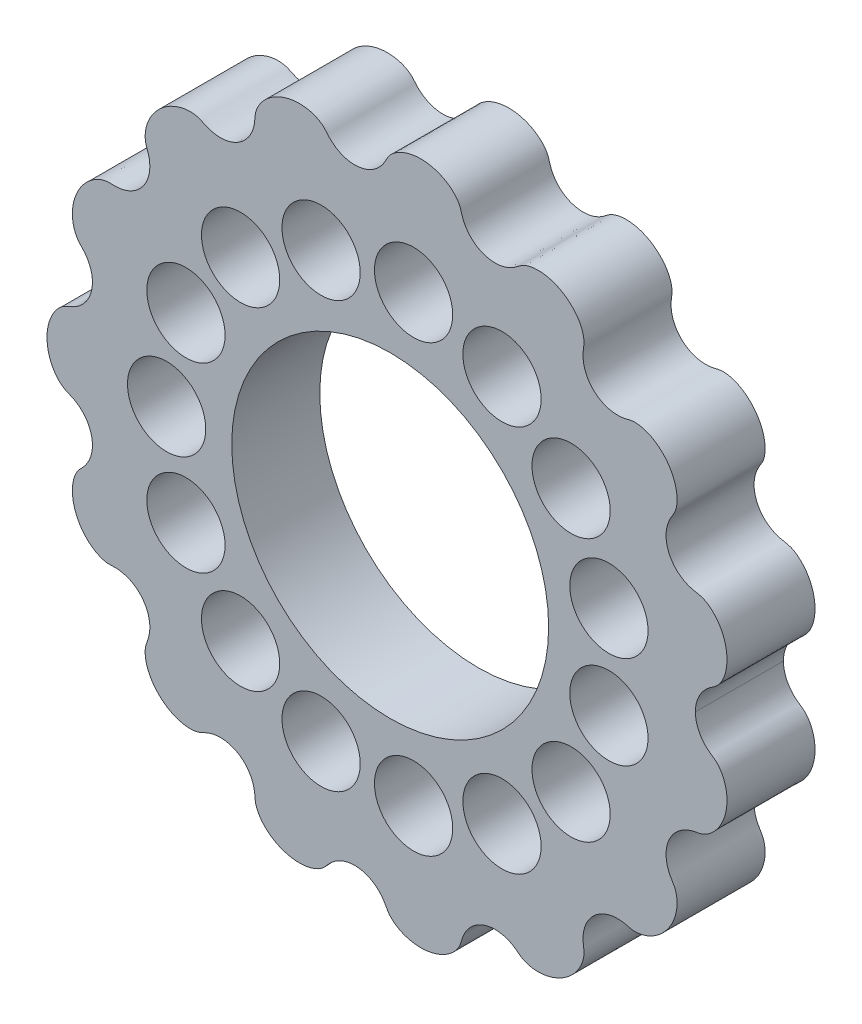
SolidWorks part; units mm, degrees
material "ABS"
ref_plane "Front Plane" through (0, 0, 0) normal (0, 0, 1) x (1, 0, 0)
ref_plane "Top Plane" through (0, 0, 0) normal (0, 1, 0) x (1, 0, 0)
ref_plane "Right Plane" through (0, 0, 0) normal (1, 0, 0) x (0, 0, -1)
sketch "Sketch2" plane through (0, 0, 0) normal (0, 0, 1) x (1, 0, 0)
  line L0 (0, 0) -> (18.3781, 0) construction
  line L1 (0, 0) -> (-12.7, 0) construction
  line L6 (0, 0) -> (-26.7529, 0) construction
  circle A0 centre (0, 0) radius 9
  circle A1 centre (-12.7, 0) radius 2.2225
  circle A10 centre (-11.602, 5.1656) radius 2.2225
  circle A11 centre (-8.498, 9.4379) radius 2.2225
  circle A12 centre (-3.9245, 12.0784) radius 2.2225
  circle A13 centre (1.3275, 12.6304) radius 2.2225
  circle A14 centre (6.35, 10.9985) radius 2.2225
  circle A15 centre (10.2745, 7.4649) radius 2.2225
  circle A16 centre (12.4225, 2.6405) radius 2.2225
  circle A17 centre (12.4225, -2.6405) radius 2.2225
  circle A18 centre (10.2745, -7.4649) radius 2.2225
  circle A19 centre (6.35, -10.9985) radius 2.2225
  circle A20 centre (1.3275, -12.6304) radius 2.2225
  circle A21 centre (-3.9245, -12.0784) radius 2.2225
  circle A22 centre (-8.498, -9.4379) radius 2.2225
  circle A23 centre (-11.602, -5.1656) radius 2.2225
  spline S0 degree 4 poles (17.3355, 0) (17.3355, 0.022) (17.3364, 0.0661) (17.3404, 0.1482) (17.3511, 0.2558) (17.3711, 0.3808) (17.4057, 0.5292) (17.4608, 0.6993) (17.5431, 0.8835) (17.6435, 1.0585) (17.7605, 1.2214) (17.8868, 1.3648) (18.0188, 1.4893) (18.152, 1.5968) (18.284, 1.6887) (18.4068, 1.7677) (18.5101, 1.8484) (18.6114, 1.9469) (18.7103, 2.0649) (18.8119, 2.2151) (18.9788, 2.5318) (19.1284, 3.0222) (19.1691, 3.6778) (19.0197, 4.3616) (18.7658, 4.895) (18.5029, 5.2499) (18.2908, 5.4667) (18.0909, 5.625) (17.936, 5.7218) (17.7996, 5.7887) (17.6725, 5.8365) (17.5499, 5.8688) (17.4098, 5.8911) (17.2557, 5.9192) (17.0952, 5.96) (16.9297, 6.0153) (16.7182, 6.1072) (16.4691, 6.2552) (16.2082, 6.4745) (15.9606, 6.7851) (15.777, 7.1489) (15.6723, 7.5479) (15.6565, 7.9135) (15.698, 8.2228) (15.7641, 8.4609) (15.8302, 8.6338) (15.9057, 8.7908) (15.9865, 8.9326) (16.0678, 9.0566) (16.1353, 9.1714) (16.1945, 9.3026) (16.2418, 9.4503) (16.2782, 9.6273) (16.3107, 9.9874) (16.2563, 10.505) (16.0255, 11.1471) (15.5906, 11.7382) (15.1094, 12.1391) (14.6943, 12.3573) (14.4005, 12.4606) (14.1434, 12.5135) (13.9574, 12.5296) (13.7955, 12.524) (13.646, 12.4991) (13.511, 12.464) (13.3614, 12.4266) (13.1944, 12.3981) (13.0154, 12.381) (12.8253, 12.3797) (12.5738, 12.4026) (12.2655, 12.4754) (11.9355, 12.6193) (11.6068, 12.8541) (11.3394, 13.1429) (11.1399, 13.4677) (11.021, 13.7866) (10.9639, 14.0781) (10.9493, 14.3167) (10.9547, 14.4996) (10.9719, 14.6649) (10.9953, 14.8125) (11.0138, 14.9707) (11.0079, 15.1399) (10.9777, 15.3255) (10.9213, 15.5246) (10.826, 15.7601) (10.6793, 16.0232) (10.4202, 16.3707) (10.0022, 16.7545) (9.5088, 17.0394) (8.9674, 17.2095) (8.5368, 17.2602) (8.2356, 17.2556) (7.9841, 17.2204) (7.7834, 17.1697) (7.6075, 17.1031) (7.4581, 17.0235) (7.3304, 16.9284) (7.2142, 16.8343) (7.0797, 16.7369) (6.924, 16.6408) (6.7101, 16.534) (6.4291, 16.4378) (6.0935, 16.3813) (5.7124, 16.3917) (5.3285, 16.4789) (4.9609, 16.6461) (4.6712, 16.86) (4.454, 17.0906) (4.3085, 17.2969) (4.2145, 17.4622) (4.1399, 17.6257) (4.0811, 17.7846) (4.0386, 17.9329) (4.0016, 18.0673) (3.9484, 18.2093) (3.8722, 18.3523) (3.7653, 18.5053) (3.5909, 18.7015) (3.3546, 18.9043) (2.9581, 19.1547) (2.3703, 19.371) (1.6409, 19.4521) (0.9694, 19.3309) (0.494, 19.1192) (0.1984, 18.911) (0.0633, 18.791) (-0.0409, 18.6762) (-0.125, 18.5593) (-0.1906, 18.4434) (-0.2573, 18.311) (-0.3397, 18.1701) (-0.438, 18.0263) (-0.5547, 17.8825) (-0.7278, 17.7063) (-0.975, 17.5157) (-1.2995, 17.3465) (-1.6974, 17.2377) (-2.1042, 17.2148) (-2.4971, 17.274) (-2.8174, 17.3902) (-3.0701, 17.532) (-3.2554, 17.6692) (-3.3861, 17.7848) (-3.5017, 17.9035) (-3.6031, 18.0229) (-3.6924, 18.133) (-3.7817, 18.2231) (-3.8867, 18.3093) (-4.0128, 18.3939) (-4.1741, 18.4797) (-4.4111, 18.5737) (-4.7049, 18.6489) (-5.1436, 18.6992) (-5.7326, 18.6523) (-6.3023, 18.4708) (-6.8174, 18.1627) (-7.1549, 17.854) (-7.3507, 17.6166) (-7.4876, 17.3991) (-7.5669, 17.236) (-7.6196, 17.0913) (-7.6543, 16.9544) (-7.6725, 16.8247) (-7.6795, 16.6788) (-7.6932, 16.5185) (-7.7196, 16.3494) (-7.7615, 16.1729) (-7.8384, 15.9445) (-7.9726, 15.6719) (-8.1825, 15.3834) (-8.486, 15.1097) (-8.8424, 14.9039) (-9.2312, 14.778) (-9.586, 14.7404) (-9.8891, 14.7605) (-10.1254, 14.8081) (-10.2992, 14.8601) (-10.4589, 14.9217) (-10.6045, 14.9901) (-10.7343, 15.0569) (-10.8558, 15.106) (-10.9917, 15.1445) (-11.1433, 15.1711) (-11.3243, 15.184) (-11.5811, 15.1742) (-11.8846, 15.1233) (-12.3207, 14.9854) (-12.845, 14.6933) (-13.2871, 14.2907) (-13.6221, 13.8041) (-13.798, 13.399) (-13.8798, 13.107) (-13.9168, 12.8547) (-13.9232, 12.6721) (-13.913, 12.5206) (-13.8908, 12.3866) (-13.8575, 12.2643) (-13.8068, 12.1318) (-13.7541, 11.9843) (-13.7091, 11.8249) (-13.6743, 11.6539) (-13.6481, 11.4248) (-13.6517, 11.135) (-13.7112, 10.7995) (-13.8564, 10.4297) (-14.0796, 10.0888) (-14.3728, 9.7987) (-14.6815, 9.6022) (-14.9702, 9.4834) (-15.2094, 9.4216) (-15.3922, 9.3924) (-15.5659, 9.3793) (-15.7291, 9.3784) (-15.8771, 9.3868) (-16.0104, 9.3879) (-16.1536, 9.3736) (-16.3051, 9.3407) (-16.4766, 9.2837) (-16.8047, 9.1318) (-17.2258, 8.8259) (-17.6664, 8.3049) (-17.9609, 7.6328) (-18.0675, 7.0156) (-18.0489, 6.547) (-17.9914, 6.2409) (-17.9088, 5.9918) (-17.8296, 5.8227) (-17.7439, 5.6853) (-17.661, 5.5845) (-17.5943, 5.5141) (-17.5308, 5.4492) (-17.4724, 5.3879) (-17.4019, 5.309) (-17.3219, 5.2104) (-17.23, 5.0812) (-17.1338, 4.9172) (-17.0279, 4.688) (-16.9368, 4.3846) (-16.8964, 4.0268) (-16.9354, 3.6248) (-17.0518, 3.2488) (-17.2333, 2.9135) (-17.4501, 2.6512) (-17.6739, 2.4559) (-17.8733, 2.324) (-18.0344, 2.2373) (-18.1861, 2.1695) (-18.3256, 2.1159) (-18.4719, 2.0529) (-18.6155, 1.9632) (-18.7611, 1.8442) (-18.9053, 1.6958) (-19.0616, 1.4955) (-19.192, 1.2774) (-19.2944, 1.0552) (-19.3719, 0.8334) (-19.4214, 0.6522) (-19.4539, 0.4901) (-19.4739, 0.3535) (-19.4855, 0.2338) (-19.4917, 0.1326) (-19.494, 0.0608) (-19.4945, 0.0203) (-19.4945, 0) knots 0.068176 0.068176 0.068176 0.068176 0.068176 0.069432 0.070688 0.071943 0.073199 0.07572 0.07824 0.080694 0.083148 0.08563 0.088113 0.090095 0.092076 0.094058 0.09604 0.097282 0.098525 0.10101 0.103607 0.106204 0.116127 0.126049 0.135533 0.140274 0.145016 0.147725 0.150434 0.152813 0.154002 0.155191 0.157122 0.159052 0.160982 0.162912 0.165276 0.167641 0.172327 0.177141 0.181961 0.187087 0.192259 0.197312 0.199858 0.202403 0.204413 0.206423 0.208433 0.210443 0.211712 0.212982 0.21552 0.21806 0.2206 0.230761 0.24092 0.251197 0.256273 0.261349 0.26392 0.26649 0.269181 0.270527 0.271873 0.273958 0.276043 0.278128 0.280213 0.282806 0.285398 0.290549 0.295754 0.300413 0.305158 0.309821 0.314419 0.31708 0.319741 0.321582 0.323422 0.325263 0.327104 0.329419 0.331734 0.334508 0.337282 0.34191 0.346537 0.355792 0.365046 0.369673 0.374301 0.377075 0.379849 0.382164 0.384479 0.38632 0.388161 0.390001 0.391842 0.394503 0.397165 0.401762 0.406425 0.41117 0.415829 0.421034 0.426185 0.428777 0.43137 0.433455 0.43554 0.437625 0.439711 0.441056 0.442402 0.445093 0.447663 0.450234 0.45531 0.460386 0.470663 0.480822 0.490983 0.493523 0.496063 0.498601 0.499871 0.50114 0.50315 0.50516 0.50717 0.50918 0.511725 0.514271 0.519324 0.524496 0.529623 0.534442 0.539256 0.543942 0.546307 0.548671 0.550601 0.552531 0.554461 0.556392 0.557581 0.55877 0.561149 0.563858 0.566567 0.571309 0.57605 0.585534 0.595456 0.600418 0.605379 0.607976 0.610573 0.613058 0.614301 0.615543 0.617525 0.619507 0.621488 0.62347 0.625953 0.628436 0.633343 0.638384 0.643407 0.648429 0.653471 0.658378 0.660861 0.663343 0.665325 0.667307 0.669288 0.67127 0.672513 0.673755 0.676241 0.678838 0.681434 0.686396 0.691357 0.701279 0.710763 0.715505 0.720246 0.722955 0.725664 0.728043 0.729232 0.730422 0.732352 0.734282 0.736212 0.738142 0.740507 0.742871 0.747557 0.752371 0.757191 0.762317 0.76749 0.772543 0.775088 0.777634 0.779644 0.781654 0.783663 0.785673 0.786943 0.788212 0.790751 0.793291 0.79583 0.805991 0.816151 0.826427 0.831503 0.83658 0.83915 0.841721 0.844412 0.845757 0.847103 0.848145 0.849188 0.85023 0.851273 0.853358 0.855443 0.858036 0.860629 0.865779 0.870984 0.875643 0.880389 0.885051 0.889649 0.89231 0.894972 0.896812 0.898653 0.900493 0.902334 0.904649 0.906964 0.909738 0.912513 0.91714 0.919454 0.921767 0.924081 0.926394 0.927551 0.928708 0.929865 0.931022 0.931022 0.931022 0.931022 0.931022
  spline S2 degree 4 poles (18.7633, 4.8586) (18.8566, 4.6949) (19.0126, 4.3502) (19.1295, 3.8883) (19.146, 3.3193) (19.0772, 2.8818) (18.9864, 2.5766) (18.8762, 2.3288) (18.7622, 2.1358) (18.6445, 1.9821) (18.5309, 1.8645) (18.4127, 1.7724) (18.2984, 1.6976) (18.1631, 1.6053) (18.0131, 1.4864) (17.8313, 1.3119) (17.6678, 1.103) (17.5417, 0.8858) (17.4501, 0.6688) (17.4009, 0.5099) (17.3699, 0.3735) (17.3511, 0.2546) (17.3405, 0.1491) (17.3351, 0.0404) (17.335, -0.0379) (17.3404, -0.1482) (17.3511, -0.2558) (17.3711, -0.3808) (17.4057, -0.5292) (17.4608, -0.6993) (17.5431, -0.8835) (17.6435, -1.0585) (17.7605, -1.2214) (17.8868, -1.3648) (18.0188, -1.4893) (18.152, -1.5968) (18.284, -1.6887) (18.4068, -1.7677) (18.5101, -1.8484) (18.6114, -1.9469) (18.7103, -2.0649) (18.8119, -2.2151) (18.9788, -2.5318) (19.1284, -3.0222) (19.1691, -3.6778) (19.0197, -4.3616) (18.7658, -4.895) (18.5029, -5.2499) (18.2908, -5.4667) (18.0909, -5.625) (17.936, -5.7218) (17.7996, -5.7887) (17.6725, -5.8365) (17.5499, -5.8688) (17.4098, -5.8911) (17.2557, -5.9192) (17.0952, -5.96) (16.9297, -6.0153) (16.7182, -6.1072) (16.4691, -6.2552) (16.2082, -6.4745) (15.9606, -6.7851) (15.777, -7.1489) (15.6723, -7.5479) (15.6565, -7.9135) (15.698, -8.2228) (15.7641, -8.4609) (15.8302, -8.6338) (15.9057, -8.7908) (15.9865, -8.9326) (16.0678, -9.0566) (16.1353, -9.1714) (16.1945, -9.3026) (16.2418, -9.4503) (16.2782, -9.6273) (16.3107, -9.9874) (16.2563, -10.505) (16.0255, -11.1471) (15.5906, -11.7382) (15.1094, -12.1391) (14.6943, -12.3573) (14.4005, -12.4606) (14.1434, -12.5135) (13.9574, -12.5296) (13.7955, -12.524) (13.646, -12.4991) (13.511, -12.464) (13.3614, -12.4266) (13.1944, -12.3981) (13.0154, -12.381) (12.8253, -12.3797) (12.5738, -12.4026) (12.2655, -12.4754) (11.9355, -12.6193) (11.6068, -12.8541) (11.3394, -13.1429) (11.1399, -13.4677) (11.021, -13.7866) (10.9639, -14.0781) (10.9493, -14.3167) (10.9547, -14.4996) (10.9719, -14.6649) (10.9953, -14.8125) (11.0138, -14.9707) (11.0079, -15.1399) (10.9777, -15.3255) (10.9213, -15.5246) (10.826, -15.7601) (10.6793, -16.0232) (10.4202, -16.3707) (10.0022, -16.7545) (9.5088, -17.0394) (8.9674, -17.2095) (8.5368, -17.2602) (8.2356, -17.2556) (7.9841, -17.2204) (7.7834, -17.1697) (7.6075, -17.1031) (7.4581, -17.0235) (7.3304, -16.9284) (7.2142, -16.8343) (7.0797, -16.7369) (6.924, -16.6408) (6.7101, -16.534) (6.4291, -16.4378) (6.0935, -16.3813) (5.7124, -16.3917) (5.3285, -16.4789) (4.9609, -16.6461) (4.6712, -16.86) (4.454, -17.0906) (4.3085, -17.2969) (4.2145, -17.4622) (4.1399, -17.6257) (4.0811, -17.7846) (4.0386, -17.9329) (4.0016, -18.0673) (3.9484, -18.2093) (3.8722, -18.3523) (3.7653, -18.5053) (3.5909, -18.7015) (3.3546, -18.9043) (2.9581, -19.1547) (2.3703, -19.371) (1.6409, -19.4521) (0.9694, -19.3309) (0.494, -19.1192) (0.1984, -18.911) (0.0633, -18.791) (-0.0409, -18.6762) (-0.125, -18.5593) (-0.1906, -18.4434) (-0.2573, -18.311) (-0.3397, -18.1701) (-0.438, -18.0263) (-0.5547, -17.8825) (-0.7278, -17.7063) (-0.975, -17.5157) (-1.2995, -17.3465) (-1.6974, -17.2377) (-2.1042, -17.2148) (-2.4971, -17.274) (-2.8174, -17.3902) (-3.0701, -17.532) (-3.2554, -17.6692) (-3.3861, -17.7848) (-3.5017, -17.9035) (-3.6031, -18.0229) (-3.6924, -18.133) (-3.7817, -18.2231) (-3.8867, -18.3093) (-4.0128, -18.3939) (-4.1741, -18.4797) (-4.4111, -18.5737) (-4.7049, -18.6489) (-5.1436, -18.6992) (-5.7326, -18.6523) (-6.3023, -18.4708) (-6.8174, -18.1627) (-7.1549, -17.854) (-7.3507, -17.6166) (-7.4876, -17.3991) (-7.5669, -17.236) (-7.6196, -17.0913) (-7.6543, -16.9544) (-7.6725, -16.8247) (-7.6795, -16.6788) (-7.6932, -16.5185) (-7.7196, -16.3494) (-7.7615, -16.1729) (-7.8384, -15.9445) (-7.9726, -15.6719) (-8.1825, -15.3834) (-8.486, -15.1097) (-8.8424, -14.9039) (-9.2312, -14.778) (-9.586, -14.7404) (-9.8891, -14.7605) (-10.1254, -14.8081) (-10.2992, -14.8601) (-10.4589, -14.9217) (-10.6045, -14.9901) (-10.7343, -15.0569) (-10.8558, -15.106) (-10.9917, -15.1445) (-11.1433, -15.1711) (-11.3243, -15.184) (-11.5811, -15.1742) (-11.8846, -15.1233) (-12.3207, -14.9854) (-12.845, -14.6933) (-13.2871, -14.2907) (-13.6221, -13.8041) (-13.798, -13.399) (-13.8798, -13.107) (-13.9168, -12.8547) (-13.9232, -12.6721) (-13.913, -12.5206) (-13.8908, -12.3866) (-13.8575, -12.2643) (-13.8068, -12.1318) (-13.7541, -11.9843) (-13.7091, -11.8249) (-13.6743, -11.6539) (-13.6481, -11.4248) (-13.6517, -11.135) (-13.7112, -10.7995) (-13.8564, -10.4297) (-14.0796, -10.0888) (-14.3728, -9.7987) (-14.6815, -9.6022) (-14.9702, -9.4834) (-15.2094, -9.4216) (-15.3922, -9.3924) (-15.5659, -9.3793) (-15.7291, -9.3784) (-15.8771, -9.3868) (-16.0104, -9.3879) (-16.1536, -9.3736) (-16.3051, -9.3407) (-16.4766, -9.2837) (-16.8047, -9.1318) (-17.2258, -8.8259) (-17.6664, -8.3049) (-17.9609, -7.6328) (-18.0675, -7.0156) (-18.0489, -6.547) (-17.9914, -6.2409) (-17.9088, -5.9918) (-17.8296, -5.8227) (-17.7439, -5.6853) (-17.661, -5.5845) (-17.5943, -5.5141) (-17.5308, -5.4492) (-17.4724, -5.3879) (-17.4019, -5.309) (-17.3219, -5.2104) (-17.23, -5.0812) (-17.1338, -4.9172) (-17.0279, -4.688) (-16.9368, -4.3846) (-16.8964, -4.0268) (-16.9354, -3.6248) (-17.0518, -3.2488) (-17.2333, -2.9135) (-17.4501, -2.6512) (-17.6739, -2.4559) (-17.8733, -2.324) (-18.0344, -2.2373) (-18.1861, -2.1695) (-18.3256, -2.1159) (-18.4719, -2.0529) (-18.6155, -1.9632) (-18.7611, -1.8442) (-18.9053, -1.6958) (-19.0616, -1.4955) (-19.192, -1.2774) (-19.2944, -1.0552) (-19.3719, -0.8334) (-19.4214, -0.6522) (-19.4539, -0.4901) (-19.4739, -0.3535) (-19.4855, -0.2338) (-19.4917, -0.1326) (-19.4948, -0.037) (-19.4948, 0.0364) (-19.4917, 0.1316) (-19.4856, 0.232) (-19.4742, 0.351) (-19.4544, 0.4867) (-19.4225, 0.6475) (-19.3737, 0.8276) (-19.2973, 1.048) (-19.1964, 1.2688) (-19.0681, 1.4857) (-18.9143, 1.6852) (-18.7725, 1.8335) (-18.6329, 1.9498) (-18.5003, 2.0363) (-18.3706, 2.0977) (-18.2504, 2.1445) (-18.1062, 2.2036) (-17.9419, 2.2842) (-17.733, 2.4112) (-17.4958, 2.6047) (-17.2705, 2.8611) (-17.0558, 3.2276) (-16.9099, 3.6914) (-16.895, 4.0854) (-16.9436, 4.3777) (-16.984, 4.5249) knots 0 0 0 0 0 0.009284 0.018569 0.023211 0.027854 0.031033 0.034213 0.036543 0.038874 0.040556 0.042237 0.043918 0.0456 0.048628 0.051656 0.056303 0.058626 0.060948 0.063272 0.064433 0.065595 0.066886 0.068176 0.069432 0.070688 0.071943 0.073199 0.07572 0.07824 0.080694 0.083148 0.08563 0.088113 0.090095 0.092076 0.094058 0.09604 0.097282 0.098525 0.10101 0.103607 0.106204 0.116127 0.126049 0.135533 0.140274 0.145016 0.147725 0.150434 0.152813 0.154002 0.155191 0.157122 0.159052 0.160982 0.162912 0.165276 0.167641 0.172327 0.177141 0.181961 0.187087 0.192259 0.197312 0.199858 0.202403 0.204413 0.206423 0.208433 0.210443 0.211712 0.212982 0.21552 0.21806 0.2206 0.230761 0.24092 0.251197 0.256273 0.261349 0.26392 0.26649 0.269181 0.270527 0.271873 0.273958 0.276043 0.278128 0.280213 0.282806 0.285398 0.290549 0.295754 0.300413 0.305158 0.309821 0.314419 0.31708 0.319741 0.321582 0.323422 0.325263 0.327104 0.329419 0.331734 0.334508 0.337282 0.34191 0.346537 0.355792 0.365046 0.369673 0.374301 0.377075 0.379849 0.382164 0.384479 0.38632 0.388161 0.390001 0.391842 0.394503 0.397165 0.401762 0.406425 0.41117 0.415829 0.421034 0.426185 0.428777 0.43137 0.433455 0.43554 0.437625 0.439711 0.441056 0.442402 0.445093 0.447663 0.450234 0.45531 0.460386 0.470663 0.480822 0.490983 0.493523 0.496063 0.498601 0.499871 0.50114 0.50315 0.50516 0.50717 0.50918 0.511725 0.514271 0.519324 0.524496 0.529623 0.534442 0.539256 0.543942 0.546307 0.548671 0.550601 0.552531 0.554461 0.556392 0.557581 0.55877 0.561149 0.563858 0.566567 0.571309 0.57605 0.585534 0.595456 0.600418 0.605379 0.607976 0.610573 0.613058 0.614301 0.615543 0.617525 0.619507 0.621488 0.62347 0.625953 0.628436 0.633343 0.638384 0.643407 0.648429 0.653471 0.658378 0.660861 0.663343 0.665325 0.667307 0.669288 0.67127 0.672513 0.673755 0.676241 0.678838 0.681434 0.686396 0.691357 0.701279 0.710763 0.715505 0.720246 0.722955 0.725664 0.728043 0.729232 0.730422 0.732352 0.734282 0.736212 0.738142 0.740507 0.742871 0.747557 0.752371 0.757191 0.762317 0.76749 0.772543 0.775088 0.777634 0.779644 0.781654 0.783663 0.785673 0.786943 0.788212 0.790751 0.793291 0.79583 0.805991 0.816151 0.826427 0.831503 0.83658 0.83915 0.841721 0.844412 0.845757 0.847103 0.848145 0.849188 0.85023 0.851273 0.853358 0.855443 0.858036 0.860629 0.865779 0.870984 0.875643 0.880389 0.885051 0.889649 0.89231 0.894972 0.896812 0.898653 0.900493 0.902334 0.904649 0.906964 0.909738 0.912513 0.91714 0.919454 0.921767 0.924081 0.926394 0.927551 0.928708 0.929865 0.931022 0.93217 0.933319 0.934467 0.935616 0.937913 0.94021 0.942507 0.944804 0.949398 0.952146 0.954894 0.957192 0.95949 0.961079 0.962667 0.964255 0.965844 0.968759 0.971674 0.976278 0.980873 0.985473 0.99248 1 1 1 1 1 construction
  spline S3 degree 4 poles (17.3355, 0) (17.3355, -0.022) (17.3364, -0.0661) (17.3404, -0.1482) (17.3511, -0.2558) (17.3711, -0.3808) (17.4057, -0.5292) (17.4608, -0.6993) (17.5431, -0.8835) (17.6435, -1.0585) (17.7605, -1.2214) (17.8868, -1.3648) (18.0188, -1.4893) (18.152, -1.5968) (18.284, -1.6887) (18.4068, -1.7677) (18.5101, -1.8484) (18.6114, -1.9469) (18.7103, -2.0649) (18.8119, -2.2151) (18.9788, -2.5318) (19.1284, -3.0222) (19.1691, -3.6778) (19.0197, -4.3616) (18.7658, -4.895) (18.5029, -5.2499) (18.2908, -5.4667) (18.0909, -5.625) (17.936, -5.7218) (17.7996, -5.7887) (17.6725, -5.8365) (17.5499, -5.8688) (17.4098, -5.8911) (17.2557, -5.9192) (17.0952, -5.96) (16.9297, -6.0153) (16.7182, -6.1072) (16.4691, -6.2552) (16.2082, -6.4745) (15.9606, -6.7851) (15.777, -7.1489) (15.6723, -7.5479) (15.6565, -7.9135) (15.698, -8.2228) (15.7641, -8.4609) (15.8302, -8.6338) (15.9057, -8.7908) (15.9865, -8.9326) (16.0678, -9.0566) (16.1353, -9.1714) (16.1945, -9.3026) (16.2418, -9.4503) (16.2782, -9.6273) (16.3107, -9.9874) (16.2563, -10.505) (16.0255, -11.1471) (15.5906, -11.7382) (15.1094, -12.1391) (14.6943, -12.3573) (14.4005, -12.4606) (14.1434, -12.5135) (13.9574, -12.5296) (13.7955, -12.524) (13.646, -12.4991) (13.511, -12.464) (13.3614, -12.4266) (13.1944, -12.3981) (13.0154, -12.381) (12.8253, -12.3797) (12.5738, -12.4026) (12.2655, -12.4754) (11.9355, -12.6193) (11.6068, -12.8541) (11.3394, -13.1429) (11.1399, -13.4677) (11.021, -13.7866) (10.9639, -14.0781) (10.9493, -14.3167) (10.9547, -14.4996) (10.9719, -14.6649) (10.9953, -14.8125) (11.0138, -14.9707) (11.0079, -15.1399) (10.9777, -15.3255) (10.9213, -15.5246) (10.826, -15.7601) (10.6793, -16.0232) (10.4202, -16.3707) (10.0022, -16.7545) (9.5088, -17.0394) (8.9674, -17.2095) (8.5368, -17.2602) (8.2356, -17.2556) (7.9841, -17.2204) (7.7834, -17.1697) (7.6075, -17.1031) (7.4581, -17.0235) (7.3304, -16.9284) (7.2142, -16.8343) (7.0797, -16.7369) (6.924, -16.6408) (6.7101, -16.534) (6.4291, -16.4378) (6.0935, -16.3813) (5.7124, -16.3917) (5.3285, -16.4789) (4.9609, -16.6461) (4.6712, -16.86) (4.454, -17.0906) (4.3085, -17.2969) (4.2145, -17.4622) (4.1399, -17.6257) (4.0811, -17.7846) (4.0386, -17.9329) (4.0016, -18.0673) (3.9484, -18.2093) (3.8722, -18.3523) (3.7653, -18.5053) (3.5909, -18.7015) (3.3546, -18.9043) (2.9581, -19.1547) (2.3703, -19.371) (1.6409, -19.4521) (0.9694, -19.3309) (0.494, -19.1192) (0.1984, -18.911) (0.0633, -18.791) (-0.0409, -18.6762) (-0.125, -18.5593) (-0.1906, -18.4434) (-0.2573, -18.311) (-0.3397, -18.1701) (-0.438, -18.0263) (-0.5547, -17.8825) (-0.7278, -17.7063) (-0.975, -17.5157) (-1.2995, -17.3465) (-1.6974, -17.2377) (-2.1042, -17.2148) (-2.4971, -17.274) (-2.8174, -17.3902) (-3.0701, -17.532) (-3.2554, -17.6692) (-3.3861, -17.7848) (-3.5017, -17.9035) (-3.6031, -18.0229) (-3.6924, -18.133) (-3.7817, -18.2231) (-3.8867, -18.3093) (-4.0128, -18.3939) (-4.1741, -18.4797) (-4.4111, -18.5737) (-4.7049, -18.6489) (-5.1436, -18.6992) (-5.7326, -18.6523) (-6.3023, -18.4708) (-6.8174, -18.1627) (-7.1549, -17.854) (-7.3507, -17.6166) (-7.4876, -17.3991) (-7.5669, -17.236) (-7.6196, -17.0913) (-7.6543, -16.9544) (-7.6725, -16.8247) (-7.6795, -16.6788) (-7.6932, -16.5185) (-7.7196, -16.3494) (-7.7615, -16.1729) (-7.8384, -15.9445) (-7.9726, -15.6719) (-8.1825, -15.3834) (-8.486, -15.1097) (-8.8424, -14.9039) (-9.2312, -14.778) (-9.586, -14.7404) (-9.8891, -14.7605) (-10.1254, -14.8081) (-10.2992, -14.8601) (-10.4589, -14.9217) (-10.6045, -14.9901) (-10.7343, -15.0569) (-10.8558, -15.106) (-10.9917, -15.1445) (-11.1433, -15.1711) (-11.3243, -15.184) (-11.5811, -15.1742) (-11.8846, -15.1233) (-12.3207, -14.9854) (-12.845, -14.6933) (-13.2871, -14.2907) (-13.6221, -13.8041) (-13.798, -13.399) (-13.8798, -13.107) (-13.9168, -12.8547) (-13.9232, -12.6721) (-13.913, -12.5206) (-13.8908, -12.3866) (-13.8575, -12.2643) (-13.8068, -12.1318) (-13.7541, -11.9843) (-13.7091, -11.8249) (-13.6743, -11.6539) (-13.6481, -11.4248) (-13.6517, -11.135) (-13.7112, -10.7995) (-13.8564, -10.4297) (-14.0796, -10.0888) (-14.3728, -9.7987) (-14.6815, -9.6022) (-14.9702, -9.4834) (-15.2094, -9.4216) (-15.3922, -9.3924) (-15.5659, -9.3793) (-15.7291, -9.3784) (-15.8771, -9.3868) (-16.0104, -9.3879) (-16.1536, -9.3736) (-16.3051, -9.3407) (-16.4766, -9.2837) (-16.8047, -9.1318) (-17.2258, -8.8259) (-17.6664, -8.3049) (-17.9609, -7.6328) (-18.0675, -7.0156) (-18.0489, -6.547) (-17.9914, -6.2409) (-17.9088, -5.9918) (-17.8296, -5.8227) (-17.7439, -5.6853) (-17.661, -5.5845) (-17.5943, -5.5141) (-17.5308, -5.4492) (-17.4724, -5.3879) (-17.4019, -5.309) (-17.3219, -5.2104) (-17.23, -5.0812) (-17.1338, -4.9172) (-17.0279, -4.688) (-16.9368, -4.3846) (-16.8964, -4.0268) (-16.9354, -3.6248) (-17.0518, -3.2488) (-17.2333, -2.9135) (-17.4501, -2.6512) (-17.6739, -2.4559) (-17.8733, -2.324) (-18.0344, -2.2373) (-18.1861, -2.1695) (-18.3256, -2.1159) (-18.4719, -2.0529) (-18.6155, -1.9632) (-18.7611, -1.8442) (-18.9053, -1.6958) (-19.0616, -1.4955) (-19.192, -1.2774) (-19.2944, -1.0552) (-19.3719, -0.8334) (-19.4214, -0.6522) (-19.4539, -0.4901) (-19.4739, -0.3535) (-19.4855, -0.2338) (-19.4917, -0.1326) (-19.494, -0.0608) (-19.4945, -0.0203) (-19.4945, 0) knots 0.068176 0.068176 0.068176 0.068176 0.068176 0.069432 0.070688 0.071943 0.073199 0.07572 0.07824 0.080694 0.083148 0.08563 0.088113 0.090095 0.092076 0.094058 0.09604 0.097282 0.098525 0.10101 0.103607 0.106204 0.116127 0.126049 0.135533 0.140274 0.145016 0.147725 0.150434 0.152813 0.154002 0.155191 0.157122 0.159052 0.160982 0.162912 0.165276 0.167641 0.172327 0.177141 0.181961 0.187087 0.192259 0.197312 0.199858 0.202403 0.204413 0.206423 0.208433 0.210443 0.211712 0.212982 0.21552 0.21806 0.2206 0.230761 0.24092 0.251197 0.256273 0.261349 0.26392 0.26649 0.269181 0.270527 0.271873 0.273958 0.276043 0.278128 0.280213 0.282806 0.285398 0.290549 0.295754 0.300413 0.305158 0.309821 0.314419 0.31708 0.319741 0.321582 0.323422 0.325263 0.327104 0.329419 0.331734 0.334508 0.337282 0.34191 0.346537 0.355792 0.365046 0.369673 0.374301 0.377075 0.379849 0.382164 0.384479 0.38632 0.388161 0.390001 0.391842 0.394503 0.397165 0.401762 0.406425 0.41117 0.415829 0.421034 0.426185 0.428777 0.43137 0.433455 0.43554 0.437625 0.439711 0.441056 0.442402 0.445093 0.447663 0.450234 0.45531 0.460386 0.470663 0.480822 0.490983 0.493523 0.496063 0.498601 0.499871 0.50114 0.50315 0.50516 0.50717 0.50918 0.511725 0.514271 0.519324 0.524496 0.529623 0.534442 0.539256 0.543942 0.546307 0.548671 0.550601 0.552531 0.554461 0.556392 0.557581 0.55877 0.561149 0.563858 0.566567 0.571309 0.57605 0.585534 0.595456 0.600418 0.605379 0.607976 0.610573 0.613058 0.614301 0.615543 0.617525 0.619507 0.621488 0.62347 0.625953 0.628436 0.633343 0.638384 0.643407 0.648429 0.653471 0.658378 0.660861 0.663343 0.665325 0.667307 0.669288 0.67127 0.672513 0.673755 0.676241 0.678838 0.681434 0.686396 0.691357 0.701279 0.710763 0.715505 0.720246 0.722955 0.725664 0.728043 0.729232 0.730422 0.732352 0.734282 0.736212 0.738142 0.740507 0.742871 0.747557 0.752371 0.757191 0.762317 0.76749 0.772543 0.775088 0.777634 0.779644 0.781654 0.783663 0.785673 0.786943 0.788212 0.790751 0.793291 0.79583 0.805991 0.816151 0.826427 0.831503 0.83658 0.83915 0.841721 0.844412 0.845757 0.847103 0.848145 0.849188 0.85023 0.851273 0.853358 0.855443 0.858036 0.860629 0.865779 0.870984 0.875643 0.880389 0.885051 0.889649 0.89231 0.894972 0.896812 0.898653 0.900493 0.902334 0.904649 0.906964 0.909738 0.912513 0.91714 0.919454 0.921767 0.924081 0.926394 0.927551 0.928708 0.929865 0.931022 0.931022 0.931022 0.931022 0.931022
  dimension "D1" = 18
  dimension "D2" = 4.445
  dimension "D3" = 12.7
  dimension "D4" = 15
  dimension "D5" = 12.7
extrude "Boss-Extrude1" add sketch "Sketch2" along normal blind 5
